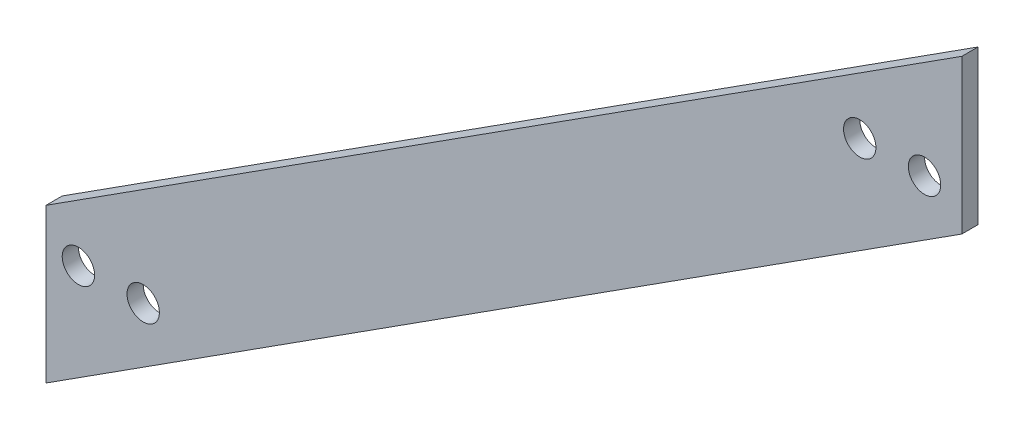
SolidWorks part; units mm, degrees
ref_plane "Front Plane" through (0, 0, 0) normal (0, 0, 1) x (1, 0, 0)
ref_plane "Top Plane" through (0, 0, 0) normal (0, 1, 0) x (1, 0, 0)
ref_plane "Right Plane" through (0, 0, 0) normal (1, 0, 0) x (0, 0, -1)
sketch "Sketch1" plane through (0, 0, 0) normal (0, 0, 1) x (1, 0, 0)
  line L0 (0, 0) -> (0, -45.2527)
  line L1 (0, -45.2527) -> (269.24, 127.2955)
  line L2 (269.24, 127.2955) -> (269.24, 172.5483)
  line L4 (269.24, 172.5483) -> (0, 0)
  line L5 (0, 0) -> (-20.5578, -13.1749) construction
  line L6 (269.24, 172.5483) -> (289.7978, 140.4704) construction
  line L7 (289.7978, 140.4704) -> (269.24, 127.2955) construction
  line L9 (-20.5578, -13.1749) -> (0, -45.2527) construction
  circle A0 centre (9.525, -10.6518) radius 4.7625
  circle A1 centre (28.575, -10.6518) radius 4.7625
  circle A2 centre (239.2348, 136.6682) radius 4.7625
  circle A3 centre (258.2848, 136.6682) radius 4.7625
  dimension "D5" = 9.525
  dimension "D9" = 9.525
  dimension "D1" = 38.1
  dimension "D2" = 147.32
  dimension "D3" = 269.24
  dimension "D4" = 319.786
  dimension "D6" = 301.4751
  dimension "D7" = 317.514
  dimension "D8" = 28.5836
  dimension "D10" = 44.6225
  dimension "D11" = 13.8023
  dimension "D12" = 344.2032
  dimension "D13" = 24.0812
extrude "Boss-Extrude1" add sketch "Sketch1" along normal blind 4.7625
